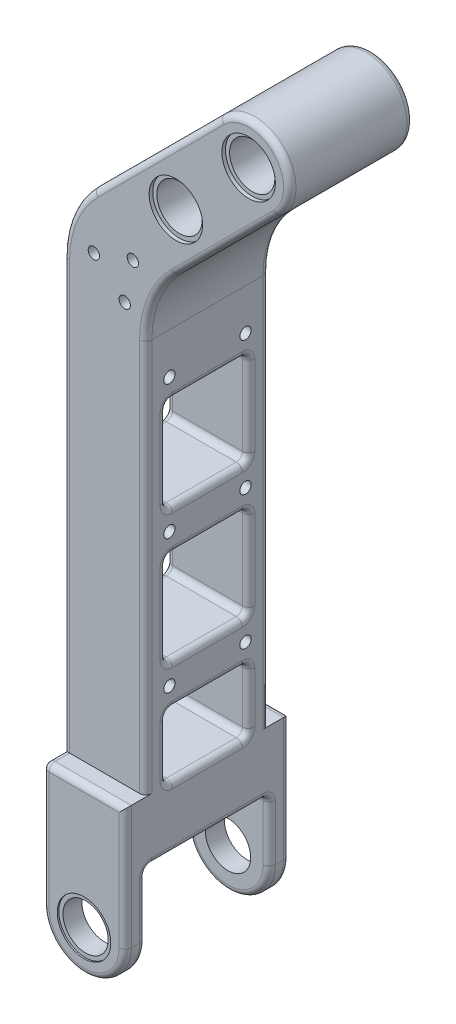
SolidWorks part; units mm, degrees
material "6061 合金"
ref_plane "前视基准面" through (0, 0, 0) normal (0, 0, 1) x (1, 0, 0)
ref_plane "上视基准面" through (0, 0, 0) normal (0, 1, 0) x (1, 0, 0)
ref_plane "右视基准面" through (0, 0, 0) normal (1, 0, 0) x (0, 0, -1)
other "Configuration Table"
sketch "草图1" plane through (0, 0, 0) normal (0, 0, 1) x (1, 0, 0)
  circle A0 centre (0, 0) radius 20
  circle A1 centre (0, 0) radius 11
  dimension "D1" = 40
  dimension "D2" = 22
extrude "凸台-拉伸1" add sketch "草图1" along normal blind 60 contours A1 | A0
ref_plane "基准面1" through (0, 0, 30) normal (0, 0, 1) x (1, 0, 0)
sketch "草图2" plane through (0, 0, 30) normal (0, 0, 1) x (1, 0, 0)
  line L0 (0, 0) -> (-70, -70) construction
  line L1 (-70, -70) -> (-70, -320) construction
  line L2 (0, -57.3148) -> (0, 49.9409) construction
  line L3 (-56.8582, 0) -> (46.4003, 0) construction
  line L4 (-14.1421, 14.1421) -> (-90, -61.7157)
  line L5 (14.1421, -14.1421) -> (-50, -78.2843)
  line L6 (-90, -61.7157) -> (-90, -320)
  line L7 (-50, -78.2843) -> (-50, -320)
  line L8 (-90, -320) -> (-50, -320)
  circle A2 centre (0, 0) radius 20 construction
  arc A3 (-14.1421, 14.1421) -> (14.1421, -14.1421) centre (0, 0) ccw
  dimension "D1" = 45
  dimension "D2" = 250
  dimension "D3" = 70
  dimension "D4" = 40
  dimension "D5" = 40
extrude "凸台-拉伸2" add sketch "草图2" along normal mid plane 60 contours L7 L8 L6 L4 A3 L5
sketch "草图4" plane through (0, 0, 60) normal (0, 0, 1) x (1, 0, 0)
  line L0 (-90, -61.7157) -> (-90, -320) construction
  line L1 (-90, -290) -> (-50, -290)
  line L2 (-90, -290) -> (-90, -350)
  line L4 (-50, -290) -> (-50, -350)
  line L5 (-50, -78.2843) -> (-50, -320) construction
  line L6 (-90, -320) -> (-50, -320) construction
  arc A0 (-90, -350) -> (-50, -350) centre (-70, -350) ccw
  circle A1 centre (-70, -350) radius 11
  dimension "D3" = 22
  dimension "D1" = 30
  dimension "D2" = 30
extrude "凸台-拉伸3" add sketch "草图4" along normal blind 10
mirror "镜向1" about plane through (0, 0, 30) normal (0, 0, 1) of "凸台-拉伸3"
sketch "草图5" plane through (0, 0, 0) normal (0, 1, 0) x (1, 0, 0)
  line L0 (0, 0) -> (0, -78.0582) construction
ref_plane "基准面2" through (-70, 0, 0) normal (-1, 0, 0) x (0, 0, 1)
sketch "草图7" plane through (-70, 0, 0) normal (-1, 0, 0) x (0, 0, 1)
  line L0 (-34.1239, -350) -> (109.535, -350) construction
sketch "草图8" plane through (0, 0, 60) normal (0, 0, 1) x (1, 0, 0)
  line L0 (0, 0) -> (-70, -70) construction
  circle A0 centre (-35.3553, -35.3553) radius 11
  dimension "D1" = 22
  dimension "D2" = 50
extrude "切除-拉伸1" cut sketch "草图8" against normal blind 100
fillet "圆角1" radius 50 2 edges at (-90, -61.7157, 30) (-50, -78.2843, 30)
fillet "圆角2" radius 3 34 edges at (-50, -320, 70) (-70, -370, 70) (-50, -335, 60) (-70, -370, 60) (-50, -335, 0) (-70, -370, 0) (-50, -320, -10) (-70, -370, -10) (-70, -320, 60) (-50, -320, 30) (-70, -320, 0) (-90, -290, 65) (-90, -320, 70) (-90, -335, 60) (-90, -320, 30) (-90, -335, 0) (-90, -320, -10) (-90, -290, -5) (-50, -194.4975, 0) (-46.194, -79.8608, 60) (-46.194, -79.8608, 0) (-10.6066, -38.8909, 0) (14.1421, 14.1421, 60) (14.1421, 14.1421, 0) (-44.7487, -16.4645, 0) (-86.194, -63.2922, 60) (-86.194, -63.2922, 0) (-90, -186.2132, 0) (-10.6066, -38.8909, 60) (-50, -194.4975, 60) (-90, -186.2132, 60) (-44.7487, -16.4645, 60) (-70, -290, 70) (-70, -290, -10)
sketch "草图9" plane through (0, 0, 70) normal (0, 0, 1) x (1, 0, 0)
  circle A0 centre (-70, -350) radius 13
  dimension "D1" = 26
extrude "切除-拉伸2" cut sketch "草图9" against normal blind 0.75
sketch "草图10" plane through (0, 0, -10) normal (0, 0, -1) x (-1, 0, 0)
  circle A0 centre (70, -350) radius 13
  dimension "D1" = 26
extrude "切除-拉伸3" cut sketch "草图10" against normal blind 0.75 contours A0
sketch "草图11" plane through (-90, 0, 0) normal (-1, 0, 0) x (0, 0, 1)
  circle A0 centre (48.5, -118.9949) radius 2.75
  circle A1 centre (48.5, -183.9949) radius 2.75
  circle A2 centre (48.5, -248.9949) radius 2.75
  circle A3 centre (11.5, -248.9949) radius 2.75
  circle A4 centre (11.5, -183.9949) radius 2.75
  circle A5 centre (11.5, -118.9949) radius 2.75
  dimension "D1" = 5.5
extrude "切除-拉伸4" cut sketch "草图11" against normal through all contours A1 | A2 | A0 | A3 | A4 | A5
sketch "草图12" plane through (-90, 0, 0) normal (-1, 0, 0) x (0, 0, 1)
  line L0 (30, -62.0134) -> (30, -339.6946) construction
  line L1 (10, -128.9949) -> (50, -128.9949)
  line L2 (10, -128.9949) -> (10, -173.9949)
  line L3 (10, -173.9949) -> (50, -173.9949)
  line L4 (50, -128.9949) -> (50, -173.9949)
  line L5 (10, -193.9949) -> (50, -193.9949)
  line L6 (10, -193.9949) -> (10, -238.9949)
  line L7 (10, -238.9949) -> (50, -238.9949)
  line L8 (50, -193.9949) -> (50, -238.9949)
  line L9 (10, -258.9949) -> (50, -258.9949)
  line L10 (10, -258.9949) -> (10, -290)
  line L11 (10, -290) -> (50, -290)
  line L12 (50, -258.9949) -> (50, -290)
  line L13 (19.5, -173.9949) -> (40.5, -173.9949)
  line L14 (19.5, -173.9949) -> (19.5, -193.9949)
  line L15 (19.5, -193.9949) -> (40.5, -193.9949)
  line L16 (40.5, -173.9949) -> (40.5, -193.9949)
  line L17 (19.5, -238.9949) -> (40.5, -238.9949)
  line L18 (19.5, -238.9949) -> (19.5, -258.9949)
  line L19 (19.5, -258.9949) -> (40.5, -258.9949)
  line L20 (40.5, -238.9949) -> (40.5, -258.9949)
  line L21 (60, -82.4264) -> (60, -290) construction
  line L22 (0, -290) -> (0, -82.4264) construction
  line L23 (57, -320) -> (3, -320) construction
  circle A0 centre (48.5, -118.9949) radius 2.75 construction
  circle A1 centre (48.5, -183.9949) radius 2.75 construction
  circle A2 centre (48.5, -248.9949) radius 2.75 construction
  dimension "D1" = 10
  dimension "D2" = 10
  dimension "D3" = 10
  dimension "D4" = 8
  dimension "D5" = 10
  dimension "D6" = 10
  dimension "D7" = 10
  dimension "D8" = 30
extrude "减重" cut sketch "草图12" against normal through all contours L0 L1 L2 L3 | L15 L0 L17 L7 L8 L5 | L0 L5 L6 L7 | L19 L0 L11 L12 L9 | L0 L9 L10 L11 | L1 L0 L13 L3 L4
fillet "圆角3" radius 3 36 edges at (-90, -258.9949, 30) (-50, -258.9949, 30) (-50, -290, 30) (-90, -290, 30) (-50, -238.9949, 30) (-50, -193.9949, 30) (-90, -193.9949, 30) (-90, -238.9949, 30) (-50, -173.9949, 30) (-90, -173.9949, 30) (-50, -128.9949, 30) (-90, -128.9949, 30) (-70, -290, 10) (-90, -274.4975, 10) (-70, -258.9949, 10) (-50, -274.4975, 10) (-50, -274.4975, 50) (-70, -258.9949, 50) (-90, -274.4975, 50) (-70, -290, 50) (-50, -216.4949, 50) (-70, -193.9949, 50) (-90, -216.4949, 50) (-70, -238.9949, 50) (-70, -238.9949, 10) (-90, -216.4949, 10) (-70, -193.9949, 10) (-50, -216.4949, 10) (-70, -173.9949, 10) (-90, -151.4949, 10) (-70, -128.9949, 10) (-50, -151.4949, 10) (-50, -151.4949, 50) (-70, -128.9949, 50) (-90, -151.4949, 50) (-70, -173.9949, 50)
sketch "草图13" plane through (0, 0, 60) normal (0, 0, 1) x (1, 0, 0)
  circle A0 centre (0, 0) radius 13
  circle A1 centre (-35.3553, -35.3553) radius 13
  dimension "D1" = 26
  dimension "D2" = 26
extrude "切除-拉伸6" cut sketch "草图13" against normal blind 1.75
sketch "草图14" plane through (0, 0, 0) normal (0, 0, -1) x (-1, 0, 0)
  circle A0 centre (0, 0) radius 13
  circle A1 centre (35.3553, -35.3553) radius 13
  dimension "D1" = 26
  dimension "D2" = 26
extrude "切除-拉伸7" cut sketch "草图14" against normal blind 1.75
sketch "草图15" plane through (0, 0, 0) normal (0, 0, -1) x (-1, 0, 0)
  line L0 (0, 0) -> (70, -350) construction
  line L1 (56.2719, -67.2005) -> (60.1942, -86.8121) construction
  line L2 (70, -350) -> (204.3541, -323.1292) construction
  circle A0 centre (56.2719, -67.2005) radius 2.75
  circle A1 centre (75.2172, -73.6095) radius 2.75
  circle A2 centre (60.1942, -86.8121) radius 2.75
  dimension "D1" = 5.5
  dimension "D2" = 20
  dimension "D3" = 20
  dimension "D4" = 20
  dimension "D5" = 42
  dimension "D6" = 270
extrude "切除-拉伸8" cut sketch "草图15" against normal through all contours A2 | A0 | A1
ref_plane "小腿主干连杆面" through (0, 0, 0) normal (0.9806, -0.1961, 0) x (0, 0, -1)
ref_plane "小腿主干对称面" through (0, 0, 30) normal (0, 0, -1) x (-1, 0, 0)
sketch "草图16" plane through (0, 0, 60) normal (0, 0, 1) x (1, 0, 0)
  line L0 (0, 0) -> (-70, -350)
  line L1 (-35.3553, -35.3553) -> (0, 0)
